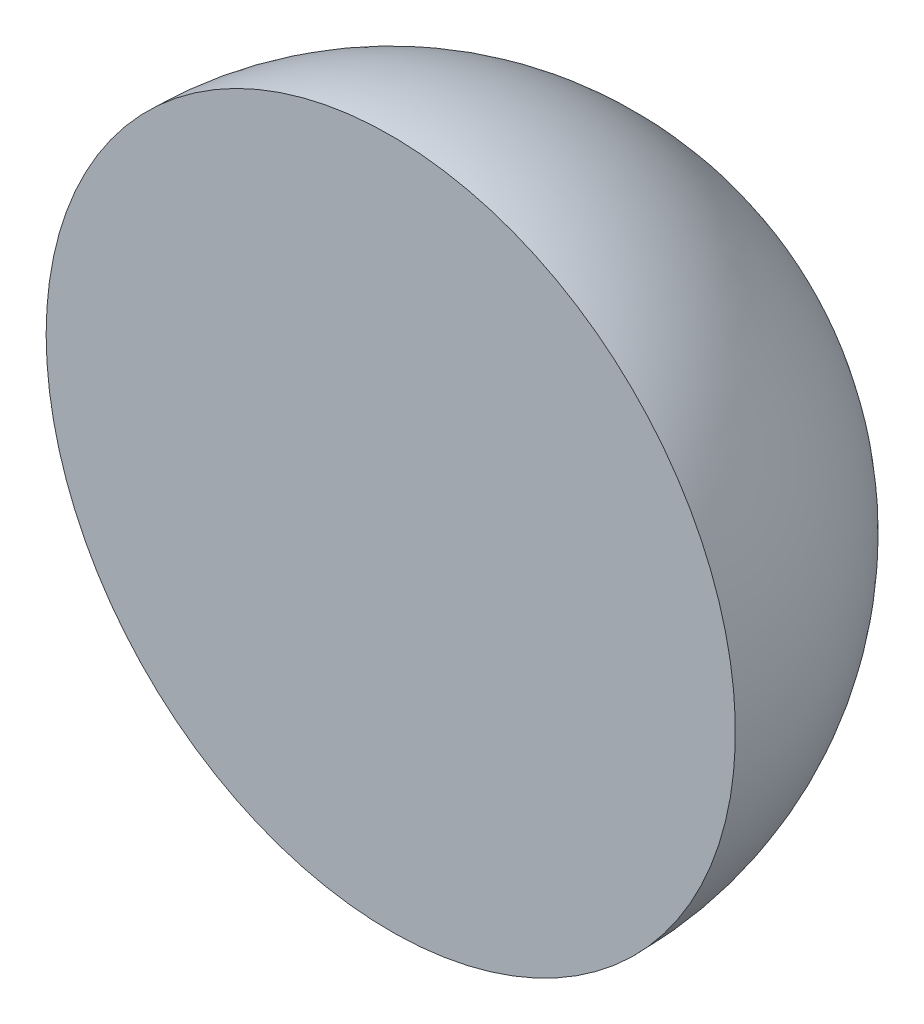
SolidWorks part; units mm, degrees
ref_plane "Front" through (0, 0, 0) normal (0, 0, 1) x (1, 0, 0)
ref_plane "Top" through (0, 0, 0) normal (0, 1, 0) x (1, 0, 0)
ref_plane "Right" through (0, 0, 0) normal (1, 0, 0) x (0, 0, -1)
sketch "Sketch2" plane through (0, 0, 0) normal (0, 0, 1) x (1, 0, 0)
  line L0 (26.955, 42.9193) -> (26.955, -25.6674) construction
  line L1 (26.955, -14.6208) -> (26.955, 35.3792)
  arc A0 (26.955, 35.3792) -> (26.955, -14.6208) centre (26.955, 10.3792) ccw
  dimension "D1" = 50
revolve "Revolve3" add sketch "Sketch2" angle 180 about L0
